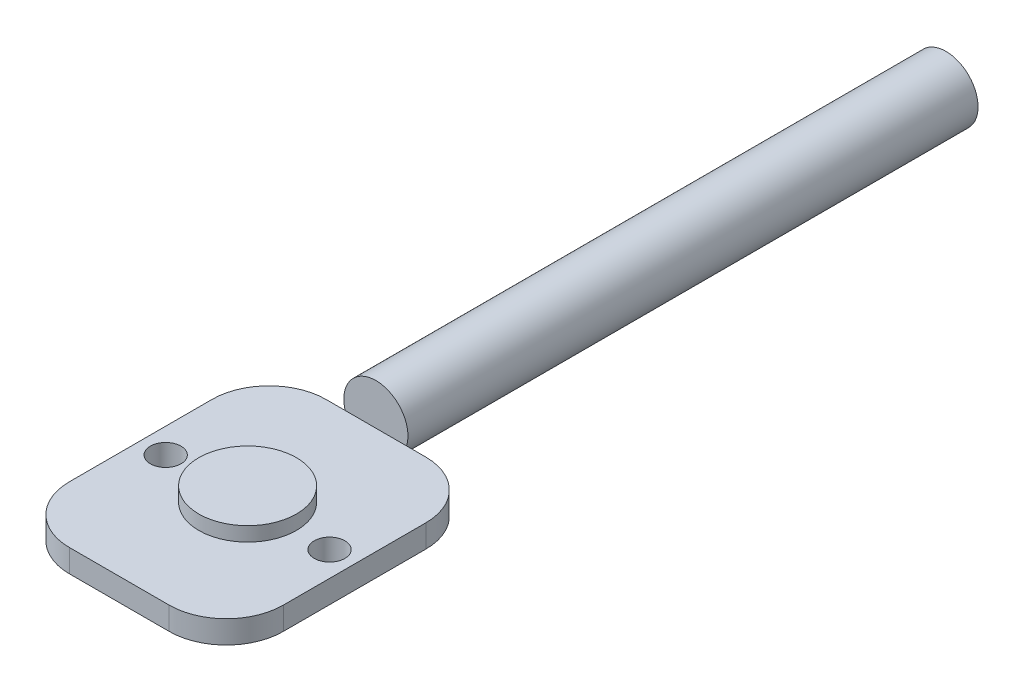
SolidWorks part; units mm, degrees
ref_plane "Front Plane" through (0, 0, 0) normal (0, 0, 1) x (1, 0, 0)
ref_plane "Top Plane" through (0, 0, 0) normal (0, 1, 0) x (1, 0, 0)
ref_plane "Right Plane" through (0, 0, 0) normal (1, 0, 0) x (0, 0, -1)
sketch "Sketch1" plane through (0, 0, 0) normal (0, 1, 0) x (1, 0, 0)
  line L0 (-3.5, 9) -> (3.5, 9)
  line L1 (7.5, 5) -> (7.5, -5)
  line L2 (3.5, -9) -> (-3.5, -9)
  line L3 (-7.5, -5) -> (-7.5, 5)
  line L4 (-7.5, 9) -> (7.5, -9) construction
  line L5 (-5.75, 0) -> (5.75, 0) construction
  arc A0 (-3.5, -9) -> (-7.5, -5) centre (-3.5, -5) cw
  arc A1 (7.5, -5) -> (3.5, -9) centre (3.5, -5) cw
  arc A2 (7.5, 5) -> (3.5, 9) centre (3.5, 5) ccw
  arc A3 (-3.5, 9) -> (-7.5, 5) centre (-3.5, 5) ccw
  circle A4 centre (-5.75, 0) radius 1.075
  circle A5 centre (5.75, 0) radius 1.075
  point P12 (7.5, 9)
  dimension "D3" = 4
  dimension "D4" = 2.15
  dimension "D1" = 15
  dimension "D2" = 18
  dimension "D5" = 11.5
extrude "Boss-Extrude1" add sketch "Sketch1" along normal blind 1.6
sketch "Sketch2" plane through (0, 1.6, 0) normal (0, 1, 0) x (1, 0, 0)
  circle A0 centre (0, 0) radius 3.4265
extrude "Boss-Extrude2" add sketch "Sketch2" along normal blind 1
sketch "Sketch4" plane through (0, 0, -9) normal (0, 0, -1) x (-1, 0, 0)
  line L3 (0, 0) -> (0, 2.25) construction
  circle A2 centre (0, 2.25) radius 2.25
  dimension "D1" = 4.5
extrude "Boss-Extrude3" add sketch "Sketch4" along normal blind 40 separate body
